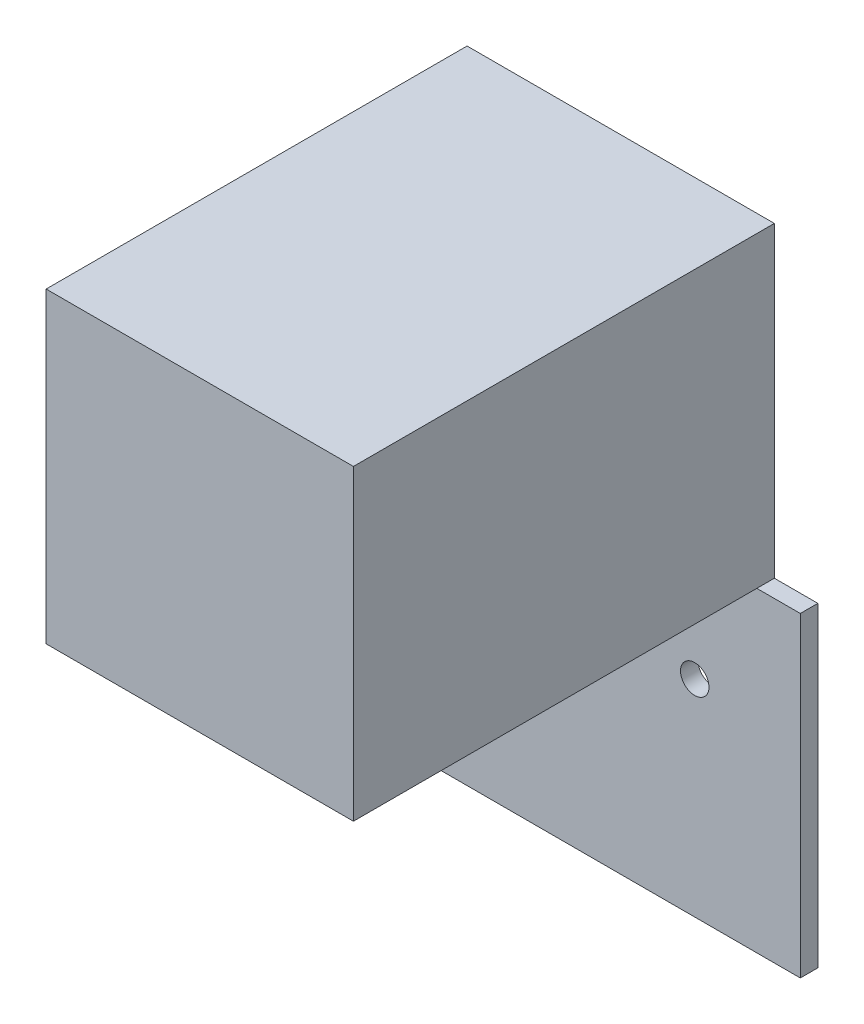
SolidWorks part; units mm, degrees
ref_plane "Front Plane" through (0, 0, 0) normal (0, 0, 1) x (1, 0, 0)
ref_plane "Top Plane" through (0, 0, 0) normal (0, 1, 0) x (1, 0, 0)
ref_plane "Right Plane" through (0, 0, 0) normal (1, 0, 0) x (0, 0, -1)
sketch "Sketch1" plane through (0, 0, 0) normal (0, 0, 1) x (1, 0, 0)
  line L1 (0, 0) -> (174.752, 0)
  line L2 (0, 0) -> (0, 114.3)
  line L3 (0, 114.3) -> (174.752, 114.3)
  line L4 (174.752, 0) -> (174.752, 114.3)
extrude "Boss-Extrude1" add sketch "Sketch1" along normal blind 6.35
sketch "Sketch2" plane through (0, 0, 0) normal (0, 0, 1) x (1, 0, 0)
  line L0 (174.752, 114.3) -> (0, 114.3) construction
  line L1 (47.752, 114.3) -> (159.004, 114.3)
  line L2 (47.752, 114.3) -> (47.752, 225.552)
  line L3 (47.752, 225.552) -> (159.004, 225.552)
  line L4 (159.004, 114.3) -> (159.004, 225.552)
extrude "Boss-Extrude2" add sketch "Sketch2" along normal blind 152.4
sketch "Sketch3" plane through (0, 0, 0) normal (0, 0, 1) x (1, 0, 0)
  circle A0 centre (73.025, 74.6252) radius 5.1562
  circle A1 centre (136.525, 74.6252) radius 5.1562
extrude "Cut-Extrude1" cut sketch "Sketch3" along normal through all
